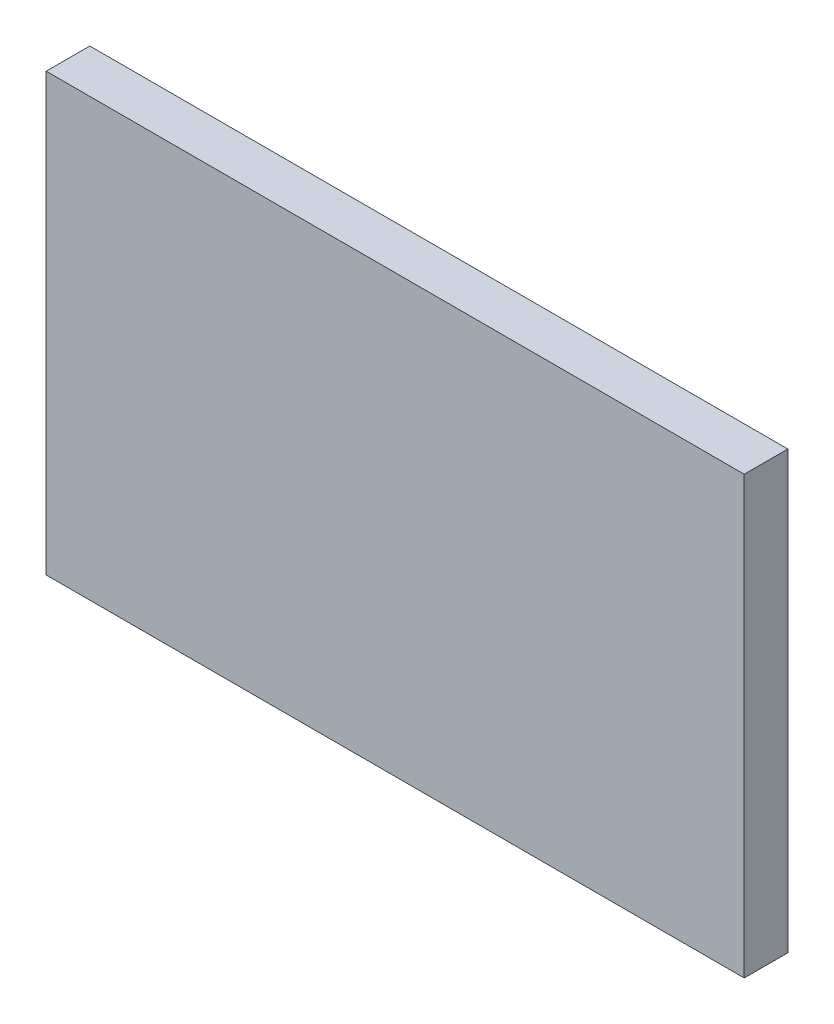
SolidWorks part; units mm, degrees
ref_plane "Front Plane" through (0, 0, 0) normal (0, 0, 1) x (1, 0, 0)
ref_plane "Top Plane" through (0, 0, 0) normal (0, 1, 0) x (1, 0, 0)
ref_plane "Right Plane" through (0, 0, 0) normal (1, 0, 0) x (0, 0, -1)
sketch "Sketch1" plane through (0, 0, 0) normal (0, 0, 1) x (1, 0, 0)
  line L1 (0, 0) -> (16, 0)
  line L2 (0, 0) -> (0, -10)
  line L3 (0, -10) -> (16, -10)
  line L4 (16, 0) -> (16, -10)
  dimension "D1" = 16
  dimension "D2" = 10
extrude "Boss-Extrude1" add sketch "Sketch1" along normal blind 1
